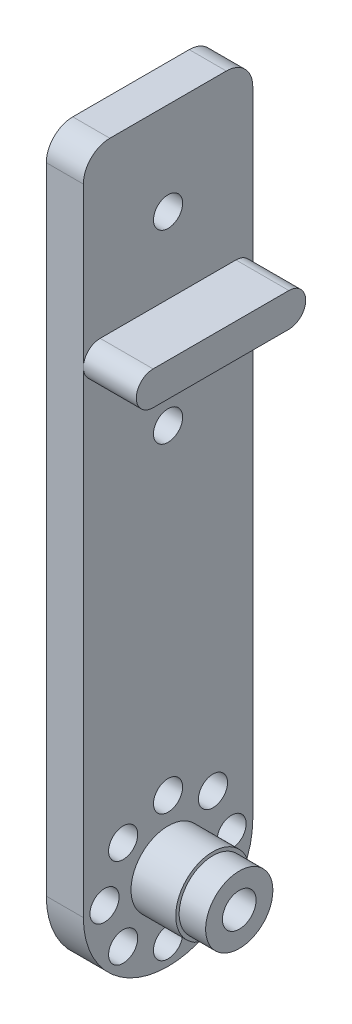
SolidWorks part; units mm, degrees
material "6061-T6 (SS)"
ref_plane "Front Plane" through (0, 0, 0) normal (0, 0, 1) x (1, 0, 0)
ref_plane "Top Plane" through (0, 0, 0) normal (0, 1, 0) x (1, 0, 0)
ref_plane "Right Plane" through (0, 0, 0) normal (1, 0, 0) x (0, 0, -1)
sketch "Sketch1" plane through (0, 0, 0) normal (1, 0, 0) x (0, 0, -1)
  line L0 (-16, 107.5) -> (16, 107.5) construction
  line L1 (-16, 72.5) -> (16, 72.5) construction
  line L3 (-11, 125) -> (11, 125)
  line L5 (0, 0) -> (50000, 0) construction
  line L6 (-16, 120) -> (-16, 0)
  line L7 (16, 120) -> (16, 0)
  circle A0 centre (0, 0) radius 16 construction
  arc A1 (-16, 0) -> (16, 0) centre (0, 0) ccw
  circle A2 centre (0, 0) radius 8 construction
  arc A3 (16, 120) -> (11, 125) centre (11, 120) ccw
  arc A4 (-16, 120) -> (-11, 125) centre (-11, 120) cw
  circle A5 centre (0, 107.5) radius 2.75
  circle A6 centre (0, 72.5) radius 2.75
  circle A7 centre (0, 12) radius 2.75
  circle A8 centre (8.4853, 8.4853) radius 2.75
  circle A9 centre (12, 0) radius 2.75
  circle A10 centre (8.4853, -8.4853) radius 2.75
  circle A11 centre (0, -12) radius 2.75
  circle A12 centre (-8.4853, -8.4853) radius 2.75
  circle A13 centre (-12, 0) radius 2.75
  circle A14 centre (-8.4853, 8.4853) radius 2.75
  point P15 (-16, 100)
  point P38 (0, 0)
  point P39 (0, 72.5)
  dimension "D1" = 32
  dimension "D5" = 5
  dimension "D7" = 5.5
  dimension "D8" = 35
  dimension "D9" = 5.5
  dimension "D10" = 16
  dimension "D11" = 5.5
  dimension "D12" = 12
  dimension "D2" = 125
  dimension "D6" = 12.5
  dimension "D13" = 8
extrude "Boss-Extrude1" add sketch "Sketch1" along normal blind 7
sketch "Sketch3" plane through (7, 0, 0) normal (1, 0, 0) x (0, 0, -1)
  circle A0 centre (0, 0) radius 7 construction
  circle A1 centre (0, 0) radius 3.175
  circle A2 centre (0, 0) radius 7
  dimension "D2" = 6.35
  dimension "D3" = 14
extrude "Boss-Extrude2" add sketch "Sketch3" along normal blind 8.449
sketch "Sketch6" plane through (15.449, 0, 0) normal (1, 0, 0) x (0, 0, -1)
  circle A0 centre (0, 0) radius 3.175
  circle A2 centre (0, 0) radius 3.175 construction
  circle A3 centre (0, 0) radius 6.35
  dimension "D1" = 6.35
extrude "Boss-Extrude4" add sketch "Sketch6" along normal blind 5
sketch "Sketch7" plane through (7, 0, 0) normal (1, 0, 0) x (0, 0, -1)
  line L0 (-12.825, 90) -> (12.825, 90) construction
  line L1 (-12.825, 93.175) -> (12.825, 93.175)
  line L2 (-12.825, 86.825) -> (12.825, 86.825)
  line L3 (0, 107.5) -> (0, 72.5) construction
  line L4 (16, 0) -> (16, 120) construction
  arc A0 (-12.825, 93.175) -> (-12.825, 86.825) centre (-12.825, 90) ccw
  arc A1 (12.825, 86.825) -> (12.825, 93.175) centre (12.825, 90) ccw
  point P2 (0, 90)
  dimension "D1" = 6.35
extrude "Boss-Extrude5" add sketch "Sketch7" along normal blind 10
